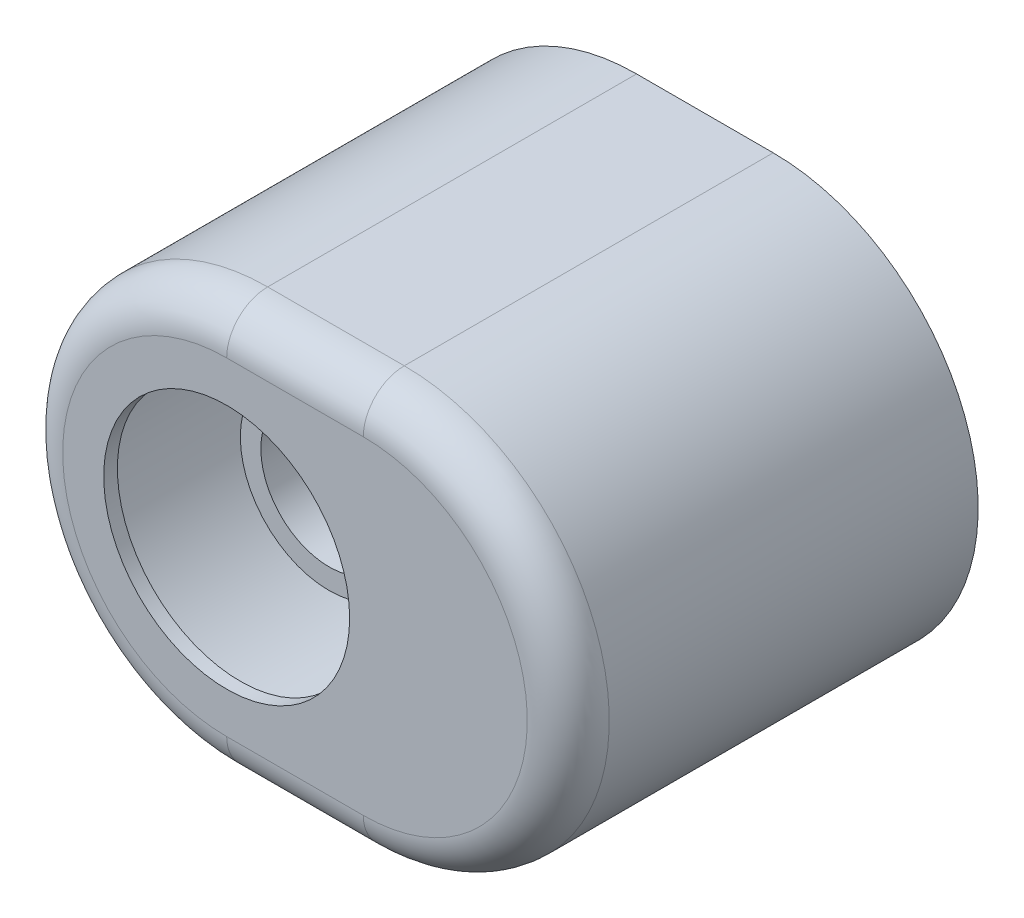
SolidWorks part; units mm, degrees
ref_plane "前视基准面" through (0, 0, 0) normal (0, 0, 1) x (1, 0, 0)
ref_plane "上视基准面" through (0, 0, 0) normal (0, 1, 0) x (1, 0, 0)
ref_plane "右视基准面" through (0, 0, 0) normal (1, 0, 0) x (0, 0, -1)
sketch "草图2" plane through (0, 0, 0) normal (0, 0, 1) x (1, 0, 0)
  line L0 (-10, 0) -> (10, 0) construction
  line L1 (-10, 30) -> (10, 30)
  line L2 (-10, -30) -> (10, -30)
  arc A0 (-10, 30) -> (-10, -30) centre (-10, 0) ccw
  arc A1 (10, -30) -> (10, 30) centre (10, 0) ccw
  point P2 (0, 0)
  dimension "D1" = 60
  dimension "D2" = 20
extrude "凸台-拉伸1" add sketch "草图2" along normal blind 60
fillet "圆角1" radius 6 4 edges at (0, 30, 60) (40, 0, 60) (0, -30, 60) (-40, 0, 60)
shell "抽壳1" thickness 2
sketch "草图3" plane through (0, 0, 60) normal (0, 0, 1) x (1, 0, 0)
  circle A0 centre (-10, 0) radius 18
  dimension "D1" = 36
extrude "切除-拉伸1" cut sketch "草图3" against normal through all
sketch "草图4" plane through (0, 0, 0) normal (0, 1, 0) x (1, 0, 0)
  line L0 (-10, 0) -> (-10, -45) construction
  line L1 (-10, -54) -> (-10, 0) construction
  line L2 (-10, -45) -> (-20, -45) construction
  line L3 (-20, -45) -> (-20, -39)
  line L4 (-20, -39) -> (-18, -39)
  line L7 (-14.5, -31) -> (-14.5, -29)
  line L8 (-14.5, -29) -> (-16.5, -29)
  line L9 (-16.5, -29) -> (-16.5, -25)
  line L10 (-16.5, -25) -> (-19.5, -25)
  line L11 (-19.5, -25) -> (-19.5, -31.6329)
  line L12 (-19.5, -31.6329) -> (-23, -37.6329)
  line L13 (-23, -37.6329) -> (-23, -45)
  line L14 (-23, -45) -> (-20, -45)
  line L15 (-18, -39) -> (-18, -37)
  line L16 (-18, -37) -> (-14.5, -31)
  line L17 (-28, -60) -> (8, -60) construction
  point P4 (-18, -36.6053)
  point P8 (-19.5, -34.997)
  point P18 (-25.2762, -43.9944)
  point P19 (0, 0)
  point P22 (-14.5, -33.1193)
  dimension "D1" = 20
  dimension "D2" = 13
  dimension "D3" = 2
  dimension "D4" = 2
  dimension "D5" = 3
  dimension "D6" = 6
  dimension "D7" = 4
  dimension "D8" = 10
  dimension "D9" = 2
  dimension "D10" = 15
  dimension "D11" = 3
  dimension "D12" = 4
revolve "旋转1" add sketch "草图4" angle 360 about L0
